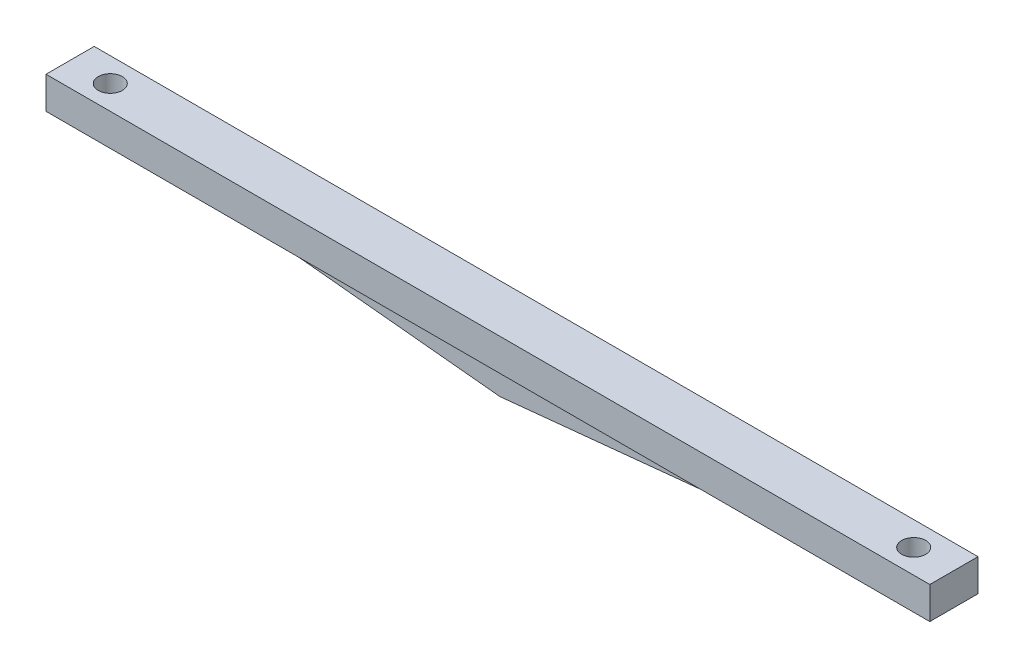
SolidWorks part; units mm, degrees
material "Plain Carbon Steel"
ref_plane "Front Plane" through (0, 0, 0) normal (0, 0, 1) x (1, 0, 0)
ref_plane "Top Plane" through (0, 0, 0) normal (0, 1, 0) x (1, 0, 0)
ref_plane "Right Plane" through (0, 0, 0) normal (1, 0, 0) x (0, 0, -1)
sketch "Sketch1" plane through (0, 0, 0) normal (0, 0, 1) x (1, 0, 0)
  line L1 (55, -2) -> (-55, -2)
  line L2 (55, -2) -> (55, 2)
  line L3 (55, 2) -> (-55, 2)
  line L4 (-55, -2) -> (-55, 2)
  line L5 (55, -2) -> (-55, 2) construction
  line L6 (55, 2) -> (-55, -2) construction
  point P0 (0, 0)
  dimension "D1" = 110
  dimension "D2" = 4
extrude "Boss-Extrude1" add sketch "Sketch1" along normal mid plane 6
sketch "Sketch2" plane through (0, 0, 0) normal (0, 0, 1) x (1, 0, 0)
  line L0 (-40, -2) -> (0, -6)
  line L1 (-55, -2) -> (55, -2) construction
  line L2 (0, -6) -> (40, -2)
  line L3 (0, -2) -> (0, -6) construction
  line L4 (-55, 2) -> (-55, -2) construction
  line L5 (-40, -2) -> (40, -2)
  dimension "D1" = 4
  dimension "D2" = 15
extrude "Boss-Extrude2" add sketch "Sketch2" along normal mid plane 3
hole_wizard "Ø3.0 (3) Diameter Hole1" positions "Sketch3" profile "Sketch4" hole size "Ø3.0" standard "ANSI Metric" end condition up to next
sketch "Sketch3" plane through (0, 2, 0) normal (0, 1, 0) x (1, 0, 0)
  line L0 (-55, -3) -> (-55, 3) construction
  line L1 (55, -3) -> (55, 3) construction
  point P0 (-50, 0)
  point P2 (50, 0)
  dimension "D1" = 5
  dimension "D2" = 5
sketch "Sketch4" plane through (-50, 2, 0) normal (1, 0, 0) x (0, 0, 1)
  line L0 (0, 0) -> (0, 4)
  line L1 (0, 4) -> (1.5, 4)
  line L2 (1.5, 4) -> (1.5, 0)
  line L5 (1.5, 0) -> (0, 0)
  line L11 (0, -6.35) -> (0, 107.95) construction
  dimension "Thru Hole Dia." = 3
  dimension "Thru Hole Depth" = 4
